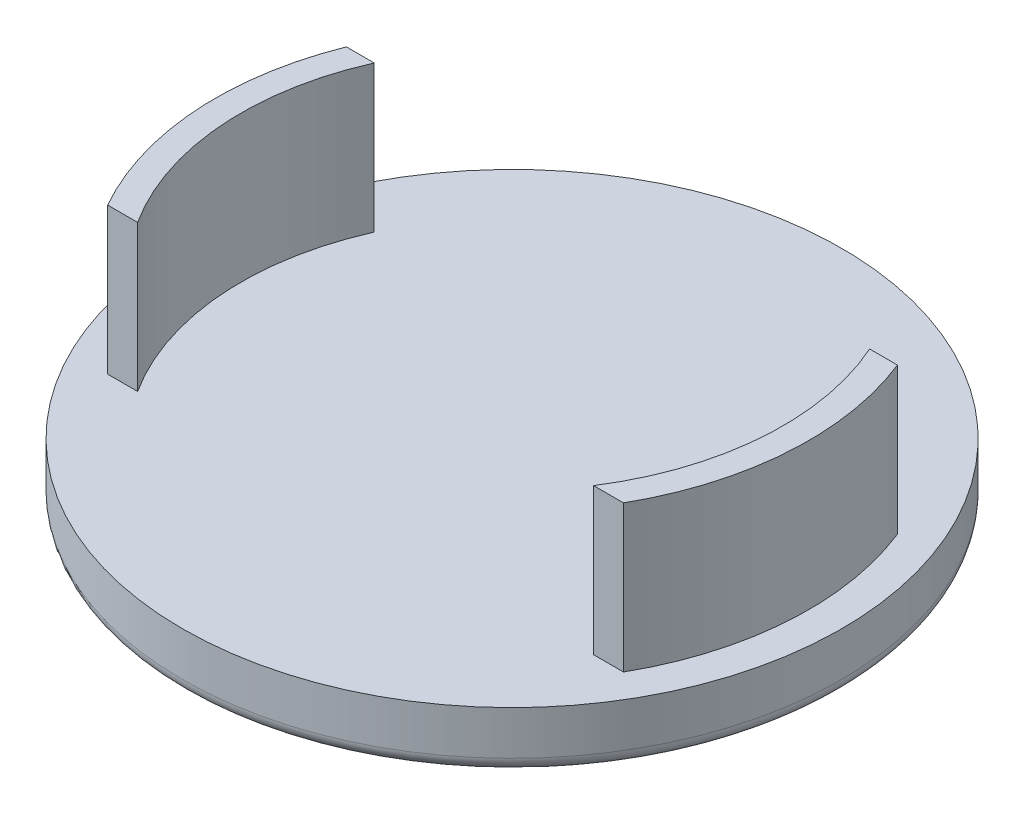
SolidWorks part; units mm, degrees
ref_plane "Front Plane" through (0, 0, 0) normal (0, 0, 1) x (1, 0, 0)
ref_plane "Top Plane" through (0, 0, 0) normal (0, 1, 0) x (1, 0, 0)
ref_plane "Right Plane" through (0, 0, 0) normal (1, 0, 0) x (0, 0, -1)
sketch "Sketch1" plane through (0, 0, 0) normal (0, 1, 0) x (1, 0, 0)
  circle A0 centre (0, 0) radius 22.5
  circle A1 centre (0, 0) radius 20.25
  circle A2 centre (0, 0) radius 18.5
  dimension "D1" = 45
  dimension "D2" = 40.5
  dimension "D3" = 37
extrude "Boss-Extrude1" add sketch "Sketch1" along normal blind 4 contours A0 A1 | A1 A2 | A2
sketch "Sketch2" plane through (0, 4, 0) normal (0, 1, 0) x (1, 0, 0)
  circle A0 centre (0, 0) radius 20.25
  circle A1 centre (0, 0) radius 18.5
  dimension "D1" = 40.5
  dimension "D2" = 37
extrude "Boss-Extrude2" add sketch "Sketch2" along normal blind 10
sketch "Sketch3" plane through (0, 14, 0) normal (0, 1, 0) x (1, 0, 0)
  line L1 (-24.1851, 23.1335) -> (22.3301, 23.1335)
  line L2 (-24.1851, 23.1335) -> (-24.1851, 7.5)
  line L3 (-24.1851, 7.5) -> (22.3301, 7.5)
  line L4 (22.3301, 23.1335) -> (22.3301, 7.5)
  line L5 (-21.2125, -10) -> (19.7979, -10)
  line L6 (-21.2125, -10) -> (-21.2125, -21.6701)
  line L7 (-21.2125, -21.6701) -> (19.7979, -21.6701)
  line L8 (19.7979, -10) -> (19.7979, -21.6701)
  dimension "D1" = 10
  dimension "D2" = 7.5
extrude "Cut-Extrude1" cut sketch "Sketch3" against normal blind 10
fillet "Fillet1" radius 1 1 edges at (0, 0, 22.5)
